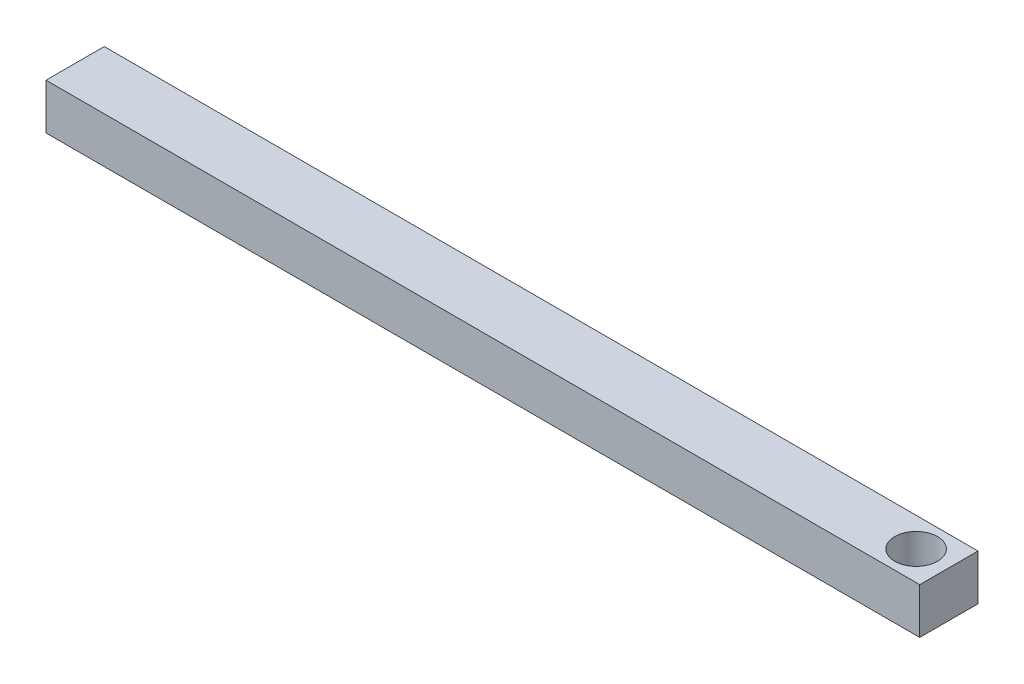
SolidWorks part; units mm, degrees
ref_plane "Front Plane" through (0, 0, 0) normal (0, 0, 1) x (1, 0, 0)
ref_plane "Top Plane" through (0, 0, 0) normal (0, 1, 0) x (1, 0, 0)
ref_plane "Right Plane" through (0, 0, 0) normal (1, 0, 0) x (0, 0, -1)
sketch "Sketch1" plane through (0, 0, 0) normal (0, 1, 0) x (1, 0, 0)
  line L1 (-30, 2) -> (30, 2)
  line L2 (-30, 2) -> (-30, -2)
  line L3 (-30, -2) -> (30, -2)
  line L4 (30, 2) -> (30, -2)
  line L5 (-30, 2) -> (30, -2) construction
  line L6 (-30, -2) -> (30, 2) construction
  circle A1 centre (27.75, 0) radius 1.47
  point P0 (0, 0)
  dimension "D1" = 4
  dimension "D3" = 2.94
  dimension "D2" = 60
  dimension "D4" = 2.25
extrude "Boss-Extrude1" add sketch "Sketch1" along normal blind 3.14
